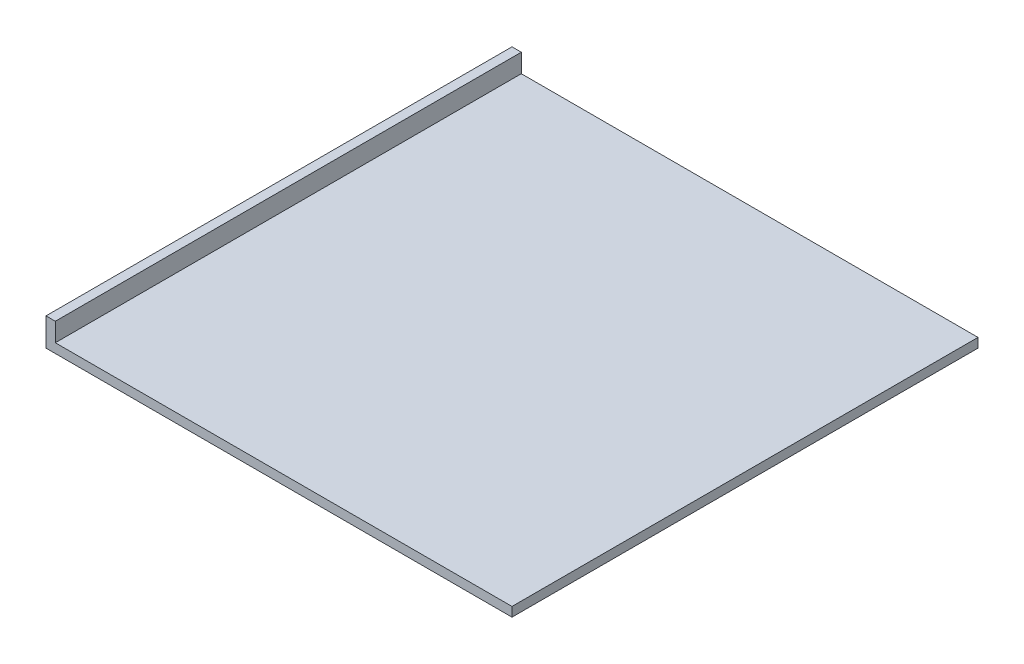
SolidWorks part; units mm, degrees
ref_plane "Front Plane" through (0, 0, 0) normal (0, 0, 1) x (1, 0, 0)
ref_plane "Top Plane" through (0, 0, 0) normal (0, 1, 0) x (1, 0, 0)
ref_plane "Right Plane" through (0, 0, 0) normal (1, 0, 0) x (0, 0, -1)
sketch "Sketch1" plane through (0, 0, 0) normal (0, 1, 0) x (1, 0, 0)
  line L1 (250, -250) -> (-250, -250)
  line L2 (250, -250) -> (250, 250)
  line L3 (250, 250) -> (-250, 250)
  line L4 (-250, -250) -> (-250, 250)
  line L5 (250, -250) -> (-250, 250) construction
  line L6 (250, 250) -> (-250, -250) construction
  point P0 (0, 0)
extrude "Boss-Extrude1" add sketch "Sketch1" along normal blind 10
sketch "Sketch2" plane through (0, 10, 0) normal (0, 1, 0) x (1, 0, 0)
  line L0 (-250, 250) -> (-250, -250)
  line L1 (-250, -250) -> (-240, -250)
  line L2 (-250, -250) -> (250, -250) construction
  line L3 (-240, -250) -> (-240, 250)
  line L4 (250, 250) -> (-250, 250) construction
  line L5 (-240, 250) -> (-250, 250)
extrude "Boss-Extrude2" add sketch "Sketch2" along normal blind 20
sketch "Sketch3" plane through (0, 0, 0) normal (0, -1, 0) x (1, 0, 0)
  line L1 (169.1514, -79.7042) -> (193.9762, -79.7042)
  line L2 (169.1514, -79.7042) -> (169.1514, -121.24)
  line L3 (169.1514, -121.24) -> (193.9762, -121.24)
  line L4 (193.9762, -79.7042) -> (193.9762, -121.24)
  line L5 (169.1514, -79.7042) -> (193.9762, -121.24) construction
  line L6 (169.1514, -121.24) -> (193.9762, -79.7042) construction
  line L7 (156.739, -136.9479) -> (181.5638, -136.9479)
  line L8 (156.739, -136.9479) -> (156.739, -184.8703)
  line L9 (156.739, -184.8703) -> (181.5638, -184.8703)
  line L10 (181.5638, -136.9479) -> (181.5638, -184.8703)
  line L11 (156.739, -136.9479) -> (181.5638, -184.8703) construction
  line L12 (156.739, -184.8703) -> (181.5638, -136.9479) construction
  line L13 (186.4371, -126.6126) -> (201.5153, -126.6126)
  line L14 (186.4371, -126.6126) -> (186.4371, -147.2833)
  line L15 (186.4371, -147.2833) -> (201.5153, -147.2833)
  line L16 (201.5153, -126.6126) -> (201.5153, -147.2833)
  line L17 (186.4371, -126.6126) -> (201.5153, -147.2833) construction
  line L18 (186.4371, -147.2833) -> (201.5153, -126.6126) construction
  point P0 (181.5638, -100.4721)
  point P5 (169.1514, -160.9091)
  point P10 (193.9762, -136.9479)
extrude "Boss-Extrude3" add sketch "Sketch3" along normal blind 10
sketch "Sketch4" plane through (0, 0, -147.2833) normal (0, 0, -1) x (-1, 0, 0)
  line L0 (-186.4371, -10) -> (-188.2003, 0)
  line L1 (-186.4371, 0) -> (-201.5153, 0) construction
  line L2 (-188.2003, 0) -> (-186.4371, 0)
  line L3 (-186.4371, 0) -> (-186.4371, -10)
  line L4 (-193.9762, 0) -> (-193.9762, -6.0725) construction
  line L5 (-199.752, 0) -> (-201.5153, 0)
  line L6 (-201.5153, 0) -> (-201.5153, -10)
  line L7 (-201.5153, -10) -> (-199.752, 0)
  dimension "D1" = 80
sketch "Sketch5" plane through (0, 0, -121.24) normal (0, 0, -1) x (-1, 0, 0)
  line L0 (-169.1514, -10) -> (-169.1514, 0)
  line L1 (-169.1514, 0) -> (-172.7911, 0)
  line L2 (-169.1514, 0) -> (-193.9762, 0) construction
  line L3 (-172.7911, 0) -> (-169.1514, -10)
  line L4 (-181.5638, 0) -> (-181.5638, -3.1247)
  line L5 (-193.9762, 0) -> (-190.3365, 0)
  line L6 (-193.9762, -10) -> (-193.9762, 0)
  line L7 (-190.3365, 0) -> (-193.9762, -10)
  line M4 (-169.1514, 0) -> (-193.9762, 0)
  line M5 (-193.9762, 0) -> (-193.9762, -10)
  line M7 (-169.1514, -10) -> (-169.1514, 0)
  dimension "D1" = 70
sketch "Sketch6" plane through (0, 0, -184.8703) normal (0, 0, -1) x (-1, 0, 0)
  line L0 (-156.739, -10) -> (-162.5125, 0)
  line L1 (-156.739, 0) -> (-181.5638, 0) construction
  line L2 (-162.5125, 0) -> (-156.739, 0)
  line L3 (-156.739, 0) -> (-156.739, -10)
  line L4 (-169.1514, 0) -> (-169.1514, -1.9047) construction
  line L5 (-175.7903, 0) -> (-181.5638, 0)
  line L6 (-181.5638, 0) -> (-181.5638, -10)
  line L7 (-181.5638, -10) -> (-175.7903, 0)
  dimension "D1" = 60
extrude "Cut-Extrude4" cut sketch "Sketch6" against normal blind 50
extrude "Cut-Extrude5" cut sketch "Sketch5" against normal blind 50 contours L3 M4 M7 | L7 M4 M5
extrude "Cut-Extrude6" cut sketch "Sketch4" against normal blind 22
